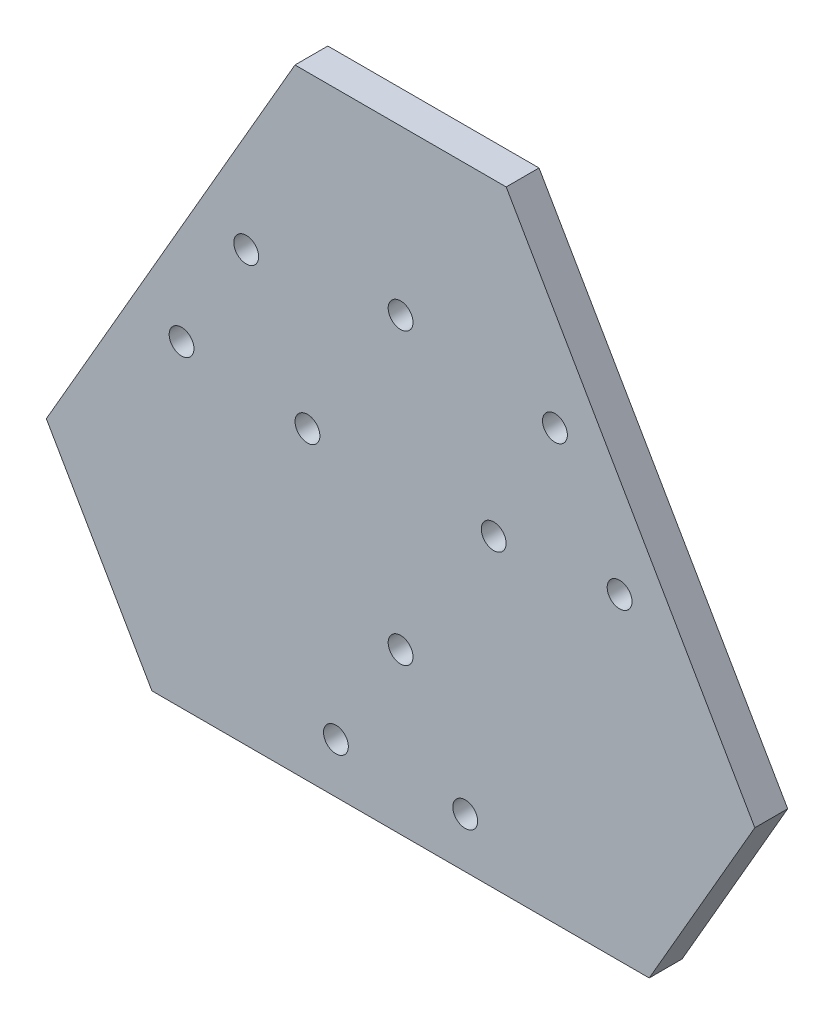
SolidWorks part; units mm, degrees
material "Pin"
ref_plane "Plan de face" through (0, 0, 0) normal (0, 0, 1) x (1, 0, 0)
ref_plane "Plan de dessus" through (0, 0, 0) normal (0, 1, 0) x (1, 0, 0)
ref_plane "Plan de droite" through (0, 0, 0) normal (1, 0, 0) x (0, 0, -1)
sketch "Esquisse1" plane through (0, 0, 0) normal (0, 0, 1) x (1, 0, 0)
  line L0 (-88.9, -51.3264) -> (0, 102.6529)
  line L1 (0, 102.6529) -> (88.9, -51.3264)
  line L2 (88.9, -51.3264) -> (-88.9, -51.3264)
  line L3 (0, 0) -> (0, -51.3264) construction
  line L4 (0, 0) -> (-44.45, 25.6632) construction
  line L5 (0, 0) -> (44.45, 25.6632) construction
  dimension "D1" = 177.8
extrude "Boss.-Extru.1" add sketch "Esquisse1" along normal blind 6.35
sketch "Esquisse2" plane through (0, 0, 6.35) normal (0, 0, 1) x (1, 0, 0)
  line L0 (-20.4159, 67.2916) -> (20.4159, 67.2916)
  line L1 (0, 102.6529) -> (-88.9, -51.3264) construction
  line L2 (88.9, -51.3264) -> (0, 102.6529) construction
  line L3 (0, 102.6529) -> (-20.4159, 67.2916)
  line L4 (20.4159, 67.2916) -> (0, 102.6529)
  line L5 (0, -51.3264) -> (0, 67.2916) construction
  line L6 (-88.9, -51.3264) -> (88.9, -51.3264) construction
  line L10 (48.0683, -51.3264) -> (88.9, -51.3264)
  line L11 (88.9, -51.3264) -> (68.4841, -15.9651)
  line L12 (68.4841, -15.9651) -> (48.0683, -51.3264)
  line L13 (-68.4841, -15.9651) -> (-88.9, -51.3264)
  line L14 (-88.9, -51.3264) -> (-48.0683, -51.3264)
  line L15 (-48.0683, -51.3264) -> (-68.4841, -15.9651)
  line L16 (58.2762, -33.6458) -> (-44.45, 25.6632) construction
  point P23 (0, 0)
  dimension "D1" = 118.618
  dimension "D2" = 3
  dimension "D3" = 118.618
extrude "Enlèv. mat.-Extru.1" cut sketch "Esquisse2" against normal through all
hole_wizard "Dégagement M41" positions "Esquisse5" profile "Esquisse4" hole size "M4" standard "Ansi Metric" end condition through all
sketch "Esquisse5" plane through (0, 0, 6.35) normal (0, 0, 1) x (1, 0, 0)
  line L0 (-48.0683, -51.3264) -> (48.0683, -51.3264) construction
  line L1 (-20.4159, 67.2916) -> (-68.4841, -15.9651) construction
  line L2 (68.4841, -15.9651) -> (20.4159, 67.2916) construction
  point P0 (12.5, -41.6744)
  point P2 (-12.5, -41.6744)
  point P16 (-42.3411, 10.0119)
  point P17 (-29.8411, 31.6625)
  point P18 (29.8411, 31.6625)
  point P19 (42.3411, 10.0119)
  dimension "D1" = 25
  dimension "D2" = 12.5
  dimension "D3" = 9.652
  dimension "D5" = 9.652
  dimension "D6" = 9.652
  dimension "D4" = 3
sketch "Esquisse4" plane through (12.5, -41.6744, 6.35) normal (1, 0, 0) x (0, -1, 0)
  line L0 (0, 0) -> (0, 6.35)
  line L1 (0, 6.35) -> (2.4, 6.35)
  line L2 (2.4, 6.35) -> (2.4, 0)
  line L5 (2.4, 0) -> (0, 0)
  line L11 (0, -6.35) -> (0, 107.95) construction
  dimension "Diamètre du perçage jusqu'au prochain" = 4.8
  dimension "Profondeur du perçage jusqu'au prochain" = 6.35
hole_wizard "Dégagement M43" positions "Esquisse9" profile "Esquisse10" hole size "M4" standard "Ansi Metric" end condition through all
sketch "Esquisse9" plane through (0, 0, 6.35) normal (0, 0, 1) x (1, 0, 0)
  point P0 (0, 35.6048)
  point P2 (0, -20.3952)
  point P4 (18, 7.6048)
  point P6 (-18, 7.6048)
  dimension "D1" = 35.6048
  dimension "D2" = 20.3952
  dimension "D3" = 18
  dimension "D4" = 18
  dimension "D5" = 7.6048
sketch "Esquisse10" plane through (0, 35.6048, 6.35) normal (1, 0, 0) x (0, -1, 0)
  line L0 (0, 0) -> (0, 6.35)
  line L1 (0, 6.35) -> (2.4, 6.35)
  line L2 (2.4, 6.35) -> (2.4, 0)
  line L5 (2.4, 0) -> (0, 0)
  line L11 (0, -6.35) -> (0, 107.95) construction
  dimension "Diamètre du perçage jusqu'au prochain" = 4.8
  dimension "Profondeur du perçage jusqu'au prochain" = 6.35
